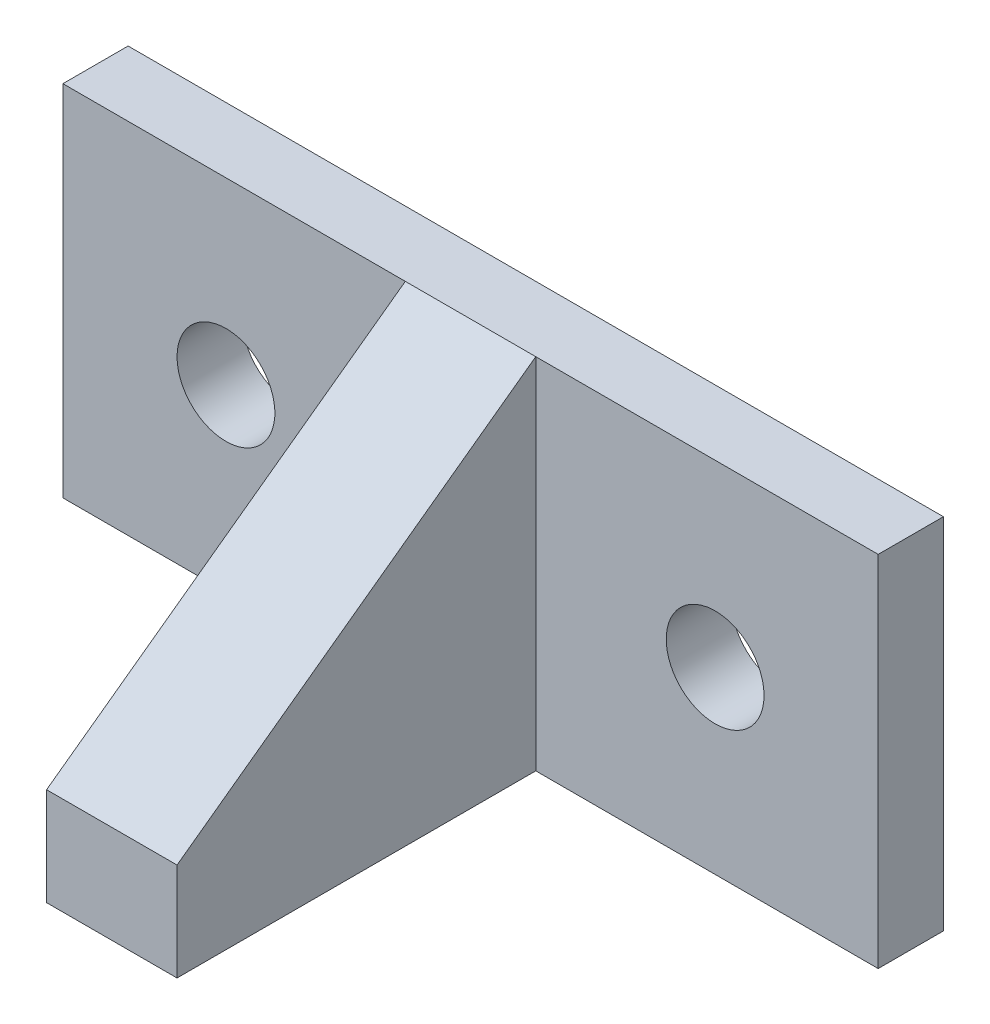
SolidWorks part; units mm, degrees
ref_plane "Front Plane" through (0, 0, 0) normal (0, 0, 1) x (1, 0, 0)
ref_plane "Top Plane" through (0, 0, 0) normal (0, 1, 0) x (1, 0, 0)
ref_plane "Right Plane" through (0, 0, 0) normal (1, 0, 0) x (0, 0, -1)
sketch "Sketch1" plane through (0, 0, 0) normal (0, 0, 1) x (1, 0, 0)
  line L0 (62.5, 0) -> (-62.5, 0) construction
  line L1 (-62.5, -27.5) -> (62.5, -27.5)
  line L2 (-62.5, -27.5) -> (-62.5, 27.5)
  line L3 (-62.5, 27.5) -> (62.5, 27.5)
  line L4 (62.5, -27.5) -> (62.5, 27.5)
  line L5 (-62.5, -27.5) -> (62.5, 27.5) construction
  line L6 (-62.5, 27.5) -> (62.5, -27.5) construction
  line L7 (0, 27.5) -> (0, -27.5) construction
  circle A0 centre (37.5, 0) radius 7.5
  circle A1 centre (-37.5, 0) radius 7.5
  point P0 (0, 0)
  point P12 (-37.5, 0)
  point P15 (0, 0)
  point P16 (0, 0)
  dimension "D3" = 75
  dimension "D1" = 125
  dimension "D2" = 55
extrude "Boss-Extrude1" add sketch "Sketch1" along normal blind 10
sketch "Sketch2" plane through (0, 0, 0) normal (1, 0, 0) x (0, 0, -1)
  line L0 (-10, -27.5) -> (-65, -27.5)
  line L1 (-65, -27.5) -> (-65, -12.5)
  line L2 (-65, -12.5) -> (-10, 27.5)
  line L3 (-10, 27.5) -> (-10, -27.5)
  dimension "D1" = 55
  dimension "D2" = 15
extrude "Boss-Extrude2" add sketch "Sketch2" along normal blind 10 and the other way blind 10
